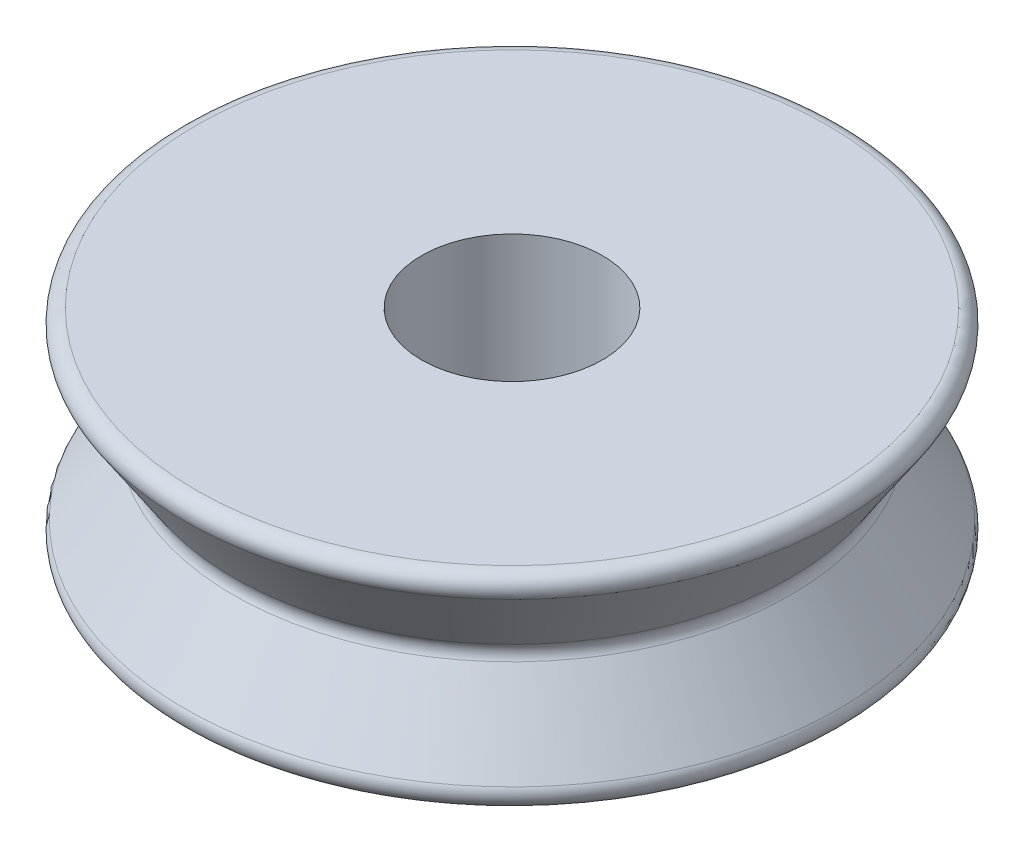
SolidWorks part; units mm, degrees
ref_plane "Plan de face" through (0, 0, 0) normal (0, 0, 1) x (1, 0, 0)
ref_plane "Plan de dessus" through (0, 0, 0) normal (0, 1, 0) x (1, 0, 0)
ref_plane "Plan de droite" through (0, 0, 0) normal (1, 0, 0) x (0, 0, -1)
sketch "Esquisse2" plane through (0, 0, 0) normal (0, 0, 1) x (1, 0, 0)
  line L0 (-10, 3) -> (-8, 0)
  line L1 (-10, 3) -> (0, 3)
  line L2 (-10, 3) -> (-10, -3) construction
  line L3 (-10, -3) -> (0, -3)
  line L4 (0, 0) -> (-8, 0) construction
  line L5 (0, 3) -> (0, -3)
  line L7 (-8, 0) -> (-10, -3)
  line L10 (0, 3) -> (0, -3) construction
  point P0 (0, 0)
  dimension "D1" = 8
  dimension "D2" = 6
  dimension "D3" = 10
revolve "Révolution1" add sketch "Esquisse2" angle 360 about L5
fillet "Congé1" radius 0.4 3 edges at (-10, 3, 0) (-8, 0, 0) (-10, -3, 0)
hole_wizard "Dégagement M51" positions "Esquisse4" profile "Esquisse3" hole size "M5" standard "Din" end condition through all
sketch "Esquisse4" plane through (0, 3, 0) normal (0, 1, 0) x (1, 0, 0)
  point P0 (0, 0)
sketch "Esquisse3" plane through (0, 3, 0) normal (1, 0, 0) x (0, 0, 1)
  line L0 (0, 0) -> (0, 6)
  line L1 (0, 6) -> (2.65, 6)
  line L2 (2.65, 6) -> (2.65, 0)
  line L5 (2.65, 0) -> (0, 0)
  line L11 (0, -6.35) -> (0, 107.95) construction
  dimension "Diamètre du perçage jusqu'au prochain" = 5.3
  dimension "Profondeur du perçage jusqu'au prochain" = 6
